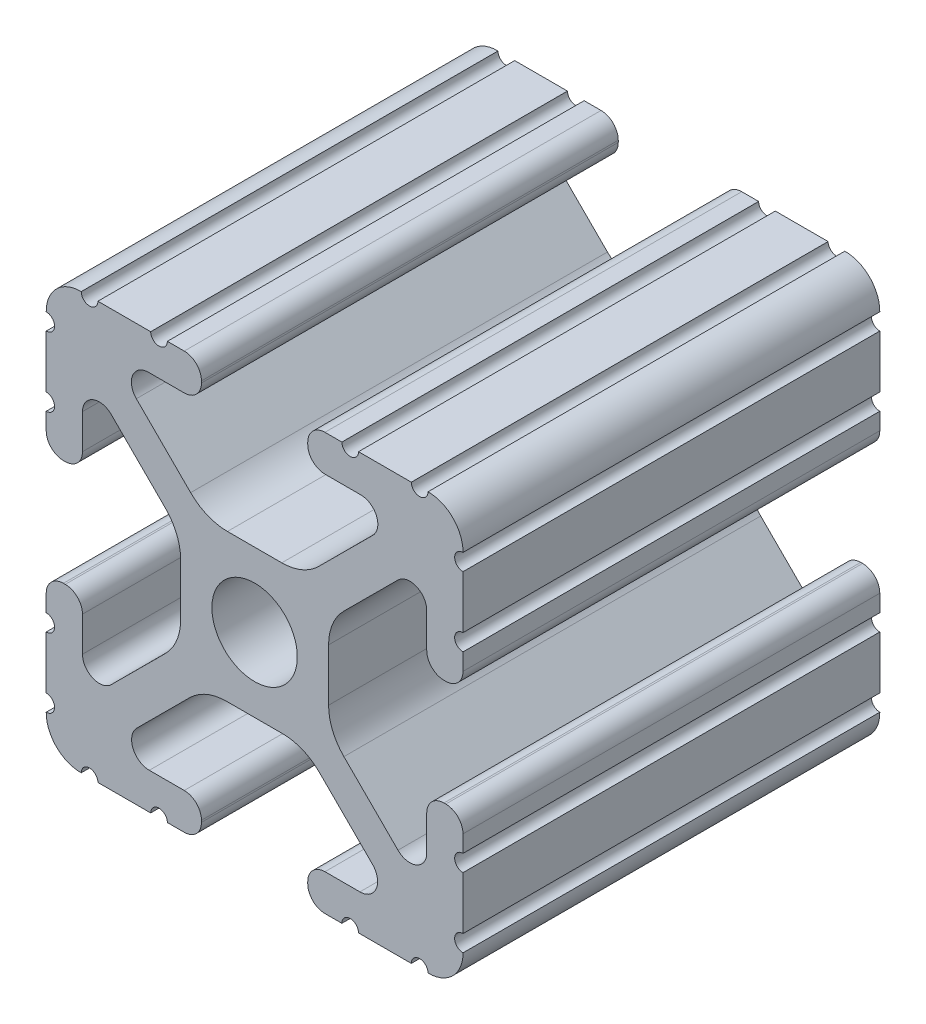
SolidWorks part; units mm, degrees
ref_plane "Front Plane" through (0, 0, 0) normal (0, 0, 1) x (1, 0, 0)
ref_plane "Top Plane" through (0, 0, 0) normal (0, 1, 0) x (1, 0, 0)
ref_plane "Right Plane" through (0, 0, 0) normal (1, 0, 0) x (0, 0, -1)
sketch "Sketch1" plane through (0, 0, 0) normal (0, 0, 1) x (1, 0, 0)
  line L88 (-7.1797, -8.6452) -> (-3.9523, -5.4237)
  line L89 (-1.7093, -4.4958) -> (1.7093, -4.4958)
  line L90 (3.9523, -5.4237) -> (7.1797, -8.6452)
  line L91 (6.4164, -10.4902) -> (4.2875, -10.4902)
  line L92 (3.2385, -11.5392) -> (3.2385, -11.651)
  line L93 (4.2875, -12.7) -> (5.3171, -12.7)
  line L94 (6.3331, -12.7) -> (9.5504, -12.7)
  line L95 (12.7, -9.5504) -> (12.7, -6.3331)
  line L96 (12.7, -5.3171) -> (12.7, -4.2875)
  line L97 (11.651, -3.2385) -> (11.5392, -3.2385)
  line L98 (10.4902, -4.2875) -> (10.4902, -6.4021)
  line L99 (8.7371, -7.1294) -> (5.441, -3.8408)
  line L100 (4.5085, -1.5932) -> (4.5085, 1.5932)
  line L101 (5.441, 3.8408) -> (8.7371, 7.1294)
  line L102 (10.4902, 6.4021) -> (10.4902, 4.2875)
  line L103 (11.5392, 3.2385) -> (11.651, 3.2385)
  line L104 (12.7, 4.2875) -> (12.7, 5.3171)
  line L105 (12.7, 6.3331) -> (12.7, 9.5504)
  line L106 (9.5504, 12.7) -> (6.3331, 12.7)
  line L107 (5.3171, 12.7) -> (4.2875, 12.7)
  line L108 (3.2385, 11.651) -> (3.2385, 11.5392)
  line L109 (4.2875, 10.4902) -> (6.4768, 10.4902)
  line L110 (7.207, 8.7244) -> (3.8983, 5.4232)
  line L111 (1.6558, 4.4958) -> (-1.6558, 4.4958)
  line L112 (-3.8983, 5.4232) -> (-7.207, 8.7244)
  line L113 (-6.4768, 10.4902) -> (-4.2875, 10.4902)
  line L114 (-3.2385, 11.5392) -> (-3.2385, 11.651)
  line L115 (-4.2875, 12.7) -> (-5.3171, 12.7)
  line L116 (-6.3331, 12.7) -> (-9.5504, 12.7)
  line L117 (-12.7, 9.5504) -> (-12.7, 6.3331)
  line L118 (-12.7, 5.3171) -> (-12.7, 4.2875)
  line L119 (-11.651, 3.2385) -> (-11.5392, 3.2385)
  line L120 (-10.4902, 4.2875) -> (-10.4902, 6.4021)
  line L121 (-8.7371, 7.1294) -> (-5.441, 3.8408)
  line L122 (-4.5085, 1.5932) -> (-4.5085, -1.5932)
  line L123 (-5.441, -3.8408) -> (-8.7371, -7.1294)
  line L124 (-10.4902, -6.4021) -> (-10.4902, -4.2875)
  line L125 (-11.5392, -3.2385) -> (-11.651, -3.2385)
  line L126 (-12.7, -4.2875) -> (-12.7, -5.3171)
  line L127 (-12.7, -6.3331) -> (-12.7, -9.5504)
  line L128 (-9.5504, -12.7) -> (-6.3331, -12.7)
  line L129 (-5.3171, -12.7) -> (-4.2875, -12.7)
  line L130 (-3.2385, -11.651) -> (-3.2385, -11.5392)
  line L131 (-4.2875, -10.4902) -> (-6.4164, -10.4902)
  circle A1 centre (0, 0) radius 2.6035
  arc A104 (-7.1797, -8.6452) -> (-6.4164, -10.4902) centre (-6.4164, -9.4098) ccw
  arc A105 (-1.7093, -4.4958) -> (-3.9523, -5.4237) centre (-1.7093, -7.6708) ccw
  arc A106 (3.9523, -5.4237) -> (1.7093, -4.4958) centre (1.7093, -7.6708) ccw
  arc A107 (6.4164, -10.4902) -> (7.1797, -8.6452) centre (6.4164, -9.4098) ccw
  arc A108 (4.2875, -10.4902) -> (3.2385, -11.5392) centre (4.2875, -11.5392) ccw
  arc A109 (3.2385, -11.651) -> (4.2875, -12.7) centre (4.2875, -11.651) ccw
  arc A110 (6.3331, -12.7) -> (5.3171, -12.7) centre (5.8251, -12.7) ccw
  arc A111 (10.5664, -12.6998) -> (9.5504, -12.7) centre (10.0584, -12.7) ccw
  arc A112 (10.5664, -12.6998) -> (12.6998, -10.5664) centre (10.5918, -10.5918) ccw
  arc A113 (12.7, -9.5504) -> (12.6998, -10.5664) centre (12.7, -10.0584) ccw
  arc A114 (12.7, -5.3171) -> (12.7, -6.3331) centre (12.7, -5.8251) ccw
  arc A115 (12.7, -4.2875) -> (11.651, -3.2385) centre (11.651, -4.2875) ccw
  arc A116 (11.5392, -3.2385) -> (10.4902, -4.2875) centre (11.5392, -4.2875) ccw
  arc A117 (8.7371, -7.1294) -> (10.4902, -6.4021) centre (9.4628, -6.4021) ccw
  arc A118 (4.5085, -1.5932) -> (5.441, -3.8408) centre (7.6835, -1.5932) ccw
  arc A119 (5.441, 3.8408) -> (4.5085, 1.5932) centre (7.6835, 1.5932) ccw
  arc A120 (10.4902, 6.4021) -> (8.7371, 7.1294) centre (9.4628, 6.4021) ccw
  arc A121 (10.4902, 4.2875) -> (11.5392, 3.2385) centre (11.5392, 4.2875) ccw
  arc A122 (11.651, 3.2385) -> (12.7, 4.2875) centre (11.651, 4.2875) ccw
  arc A123 (12.7, 6.3331) -> (12.7, 5.3171) centre (12.7, 5.8251) ccw
  arc A124 (12.6998, 10.5664) -> (12.7, 9.5504) centre (12.7, 10.0584) ccw
  arc A125 (12.6998, 10.5664) -> (10.5664, 12.6998) centre (10.5918, 10.5918) ccw
  arc A126 (9.5504, 12.7) -> (10.5664, 12.6998) centre (10.0584, 12.7) ccw
  arc A127 (5.3171, 12.7) -> (6.3331, 12.7) centre (5.8251, 12.7) ccw
  arc A128 (4.2875, 12.7) -> (3.2385, 11.651) centre (4.2875, 11.651) ccw
  arc A129 (3.2385, 11.5392) -> (4.2875, 10.4902) centre (4.2875, 11.5392) ccw
  arc A130 (7.207, 8.7244) -> (6.4768, 10.4902) centre (6.4768, 9.4563) ccw
  arc A131 (1.6558, 4.4958) -> (3.8983, 5.4232) centre (1.6558, 7.6708) ccw
  arc A132 (-3.8983, 5.4232) -> (-1.6558, 4.4958) centre (-1.6558, 7.6708) ccw
  arc A133 (-6.4768, 10.4902) -> (-7.207, 8.7244) centre (-6.4768, 9.4563) ccw
  arc A134 (-4.2875, 10.4902) -> (-3.2385, 11.5392) centre (-4.2875, 11.5392) ccw
  arc A135 (-3.2385, 11.651) -> (-4.2875, 12.7) centre (-4.2875, 11.651) ccw
  arc A136 (-6.3331, 12.7) -> (-5.3171, 12.7) centre (-5.8251, 12.7) ccw
  arc A137 (-10.5664, 12.6998) -> (-9.5504, 12.7) centre (-10.0584, 12.7) ccw
  arc A138 (-10.5664, 12.6998) -> (-12.6998, 10.5664) centre (-10.5918, 10.5918) ccw
  arc A139 (-12.7, 9.5504) -> (-12.6998, 10.5664) centre (-12.7, 10.0584) ccw
  arc A140 (-12.7, 5.3171) -> (-12.7, 6.3331) centre (-12.7, 5.8251) ccw
  arc A141 (-12.7, 4.2875) -> (-11.651, 3.2385) centre (-11.651, 4.2875) ccw
  arc A142 (-11.5392, 3.2385) -> (-10.4902, 4.2875) centre (-11.5392, 4.2875) ccw
  arc A143 (-8.7371, 7.1294) -> (-10.4902, 6.4021) centre (-9.4628, 6.4021) ccw
  arc A144 (-4.5085, 1.5932) -> (-5.441, 3.8408) centre (-7.6835, 1.5932) ccw
  arc A145 (-5.441, -3.8408) -> (-4.5085, -1.5932) centre (-7.6835, -1.5932) ccw
  arc A146 (-10.4902, -6.4021) -> (-8.7371, -7.1294) centre (-9.4628, -6.4021) ccw
  arc A147 (-10.4902, -4.2875) -> (-11.5392, -3.2385) centre (-11.5392, -4.2875) ccw
  arc A148 (-11.651, -3.2385) -> (-12.7, -4.2875) centre (-11.651, -4.2875) ccw
  arc A149 (-12.7, -6.3331) -> (-12.7, -5.3171) centre (-12.7, -5.8251) ccw
  arc A150 (-12.6998, -10.5664) -> (-12.7, -9.5504) centre (-12.7, -10.0584) ccw
  arc A151 (-12.6998, -10.5664) -> (-10.5664, -12.6998) centre (-10.5918, -10.5918) ccw
  arc A152 (-9.5504, -12.7) -> (-10.5664, -12.6998) centre (-10.0584, -12.7) ccw
  arc A153 (-5.3171, -12.7) -> (-6.3331, -12.7) centre (-5.8251, -12.7) ccw
  arc A154 (-4.2875, -12.7) -> (-3.2385, -11.651) centre (-4.2875, -11.651) ccw
  arc A155 (-3.2385, -11.5392) -> (-4.2875, -10.4902) centre (-4.2875, -11.5392) ccw
extrude "Boss-Extrude1" add sketch "Sketch1" along normal mid plane 304.8
sketch "Sketch2" plane through (0, 0, 152.4) normal (0, 0, 1) x (1, 0, 0)
  line L1 (-13.8749, 14.9541) -> (13.8749, 14.9541)
  line L2 (-13.8749, 14.9541) -> (-13.8749, -13.952)
  line L3 (-13.8749, -13.952) -> (13.8749, -13.952)
  line L4 (13.8749, 14.9541) -> (13.8749, -13.952)
extrude "Cut-Extrude1" cut sketch "Sketch2" against normal blind 279.4
